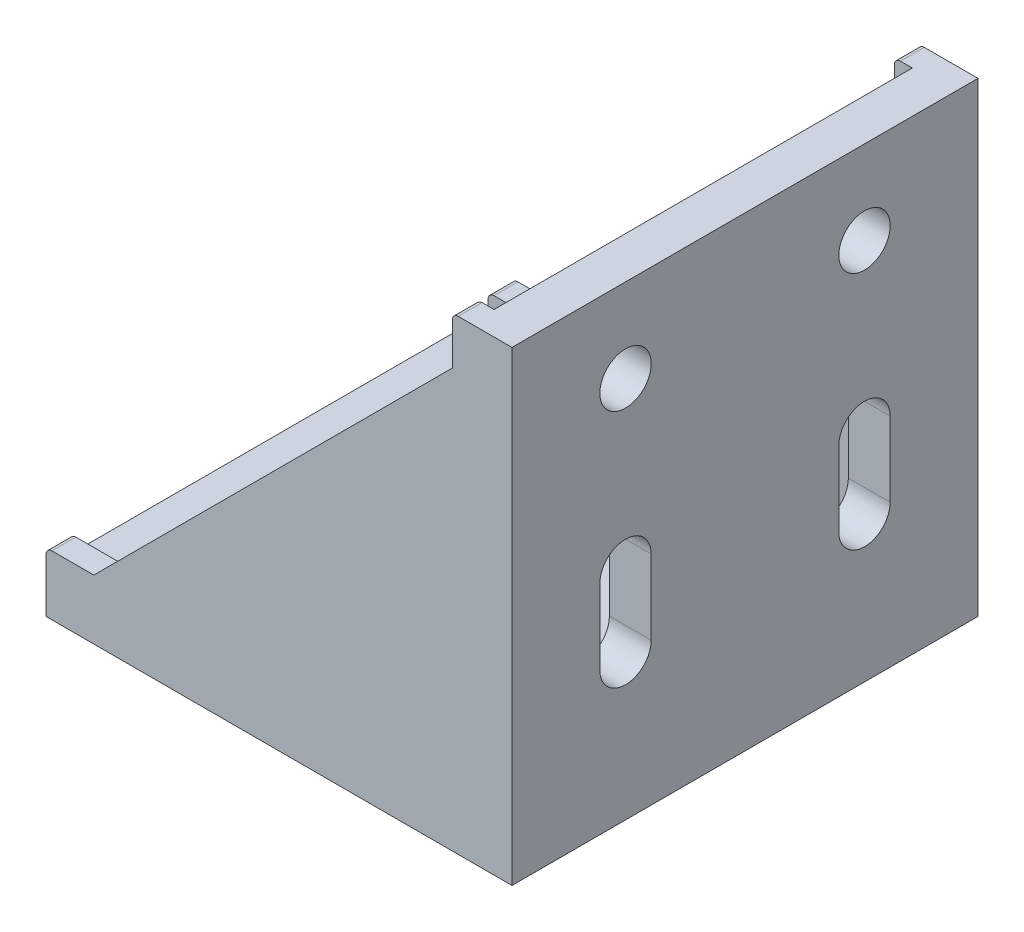
SolidWorks part; units mm, degrees
ref_plane "前视基准面" through (0, 0, 0) normal (0, 0, 1) x (1, 0, 0)
ref_plane "上视基准面" through (0, 0, 0) normal (0, 1, 0) x (1, 0, 0)
ref_plane "右视基准面" through (0, 0, 0) normal (1, 0, 0) x (0, 0, -1)
other "Configuration Table"
sketch "草图1" plane through (0, 0, 0) normal (0, 0, 1) x (1, 0, 0)
  line L0 (0, 0) -> (-78, 0)
  line L1 (-78, 0) -> (-78, 10)
  line L2 (-78, 10) -> (-70, 10)
  line L3 (-70, 10) -> (-10, 70)
  line L4 (-10, 70) -> (-10, 78)
  line L5 (-10, 78) -> (0, 78)
  line L6 (0, 78) -> (0, 0)
  dimension "D1" = 78
  dimension "D2" = 78
  dimension "D3" = 8
  dimension "D4" = 8
  dimension "D5" = 45
  dimension "D6" = 10
extrude "凸台-拉伸1" add sketch "草图1" along normal blind 78
ref_plane "基准面1" through (0, 0, 39) normal (0, 0, 1) x (1, 0, 0)
sketch "草图2" plane through (0, 0, 39) normal (0, 0, 1) x (1, 0, 0)
  line L0 (0, 0) -> (0, 78) construction
  line L1 (-83.8627, 86.9117) -> (-7, 86.9117)
  line L2 (-83.8627, 86.9117) -> (-83.8627, 7)
  line L3 (-83.8627, 7) -> (-7, 7)
  line L4 (-7, 86.9117) -> (-7, 7)
  line L5 (-83.8627, 86.9117) -> (-7, 7) construction
  line L6 (-83.8627, 7) -> (-7, 86.9117) construction
  line L7 (-78, 0) -> (0, 0) construction
  point P0 (-45.4314, 46.9558)
  dimension "D1" = 7
  dimension "D2" = 7
extrude "切除-拉伸1" cut sketch "草图2" against normal mid plane 70
fillet "圆角1" radius 1 4 edges at (-78, 10, 2) (-78, 10, 76) (-10, 78, 2) (-10, 78, 76)
sketch "草图3" plane through (0, 0, 0) normal (1, 0, 0) x (0, 0, -1)
  line L0 (-39, 93.0717) -> (-39, -23.7547) construction
  line L1 (-14.7, 36.4) -> (-14.7, 23.9)
  line L2 (-23.3, 36.4) -> (-23.3, 23.9)
  line L3 (-78, 78) -> (0, 78) construction
  line L4 (-54.7, 36.4) -> (-54.7, 23.9)
  line L5 (-63.3, 36.4) -> (-63.3, 23.9)
  circle A0 centre (-19, 64) radius 4.3
  arc A1 (-14.7, 36.4) -> (-23.3, 36.4) centre (-19, 36.4) ccw
  arc A2 (-23.3, 23.9) -> (-14.7, 23.9) centre (-19, 23.9) ccw
  arc A3 (-54.7, 23.9) -> (-63.3, 23.9) centre (-59, 23.9) cw
  arc A4 (-63.3, 36.4) -> (-54.7, 36.4) centre (-59, 36.4) cw
  circle A5 centre (-59, 64) radius 4.3
  dimension "D2" = 8.6
  dimension "D1" = 39
  dimension "D3" = 20
  dimension "D4" = 14
  dimension "D5" = 12.5
  dimension "D6" = 27.6
extrude "切除-拉伸2" cut sketch "草图3" against normal mid plane 70
sketch "草图4" plane through (0, 0, 0) normal (0, -1, 0) x (1, 0, 0)
  line L0 (-83.249, 39) -> (2.6752, 39) construction
  line L1 (-78, 0) -> (0, 0) construction
  line L2 (-36.4, 63.3) -> (-23.9, 63.3)
  line L3 (-36.4, 54.7) -> (-23.9, 54.7)
  line L4 (-78, 78) -> (-78, 0) construction
  line L5 (-36.4, 23.3) -> (-23.9, 23.3)
  line L6 (-36.4, 14.7) -> (-23.9, 14.7)
  circle A0 centre (-64, 59) radius 4.3
  arc A1 (-36.4, 63.3) -> (-36.4, 54.7) centre (-36.4, 59) ccw
  arc A2 (-23.9, 54.7) -> (-23.9, 63.3) centre (-23.9, 59) ccw
  arc A3 (-23.9, 23.3) -> (-23.9, 14.7) centre (-23.9, 19) cw
  arc A4 (-36.4, 14.7) -> (-36.4, 23.3) centre (-36.4, 19) cw
  circle A5 centre (-64, 19) radius 4.3
  dimension "D2" = 8.6
  dimension "D1" = 39
  dimension "D3" = 14
  dimension "D4" = 27.6
  dimension "D5" = 12.5
  dimension "D6" = 20
extrude "切除-拉伸3" cut sketch "草图4" against normal mid plane 70
